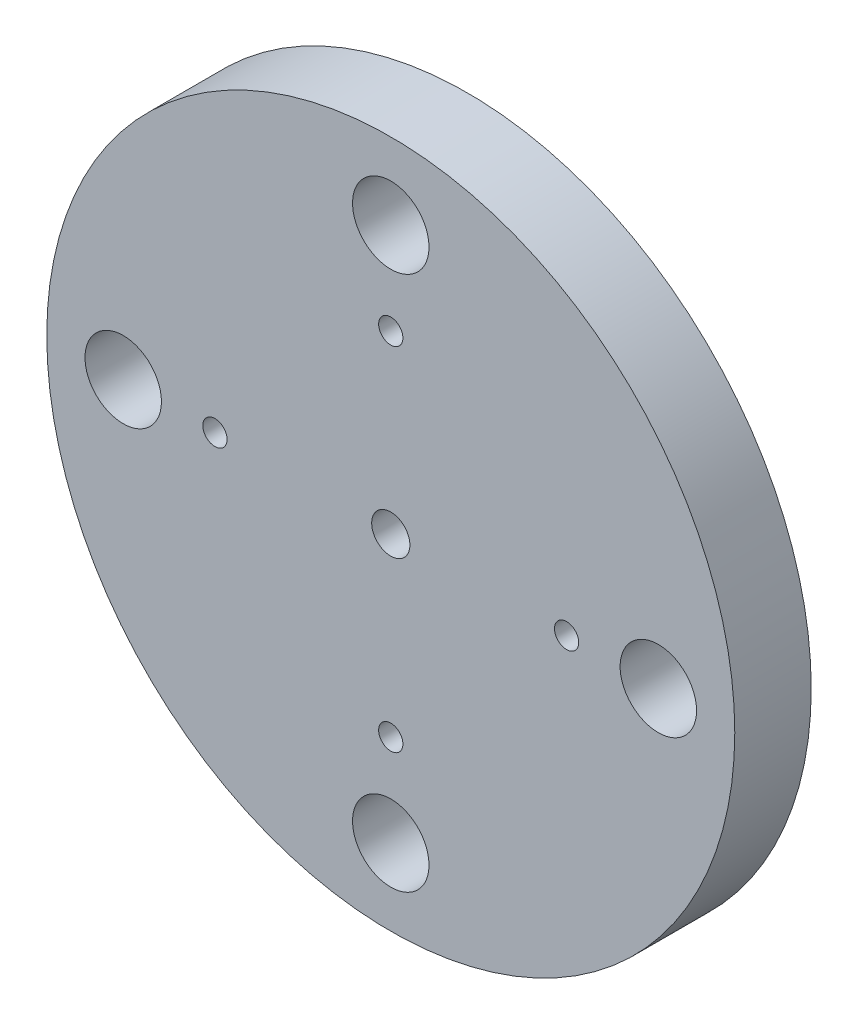
SolidWorks part; units mm, degrees
ref_plane "Front Plane" through (0, 0, 0) normal (0, 0, 1) x (1, 0, 0)
ref_plane "Top Plane" through (0, 0, 0) normal (0, 1, 0) x (1, 0, 0)
ref_plane "Right Plane" through (0, 0, 0) normal (1, 0, 0) x (0, 0, -1)
sketch "Sketch2" plane through (0, 0, 0) normal (0, 0, 1) x (1, 0, 0)
  circle A0 centre (0, 0) radius 45
  dimension "D1" = 90
extrude "Boss-Extrude1" add sketch "Sketch2" along normal blind 10
sketch "Sketch3" plane through (0, 0, 0) normal (0, 0, -1) x (-1, 0, 0)
  circle A0 centre (0, 0) radius 2.5
  dimension "D1" = 5
extrude "Cut-Extrude1" cut sketch "Sketch3" against normal through all
sketch "Sketch4" plane through (0, 0, 10) normal (0, 0, 1) x (1, 0, 0)
  circle A0 centre (0, 35) radius 5
  circle A1 centre (35, 0) radius 5
  circle A2 centre (0, -35) radius 5
  circle A3 centre (-35, 0) radius 5
  point P12 (0, 0)
  dimension "D1" = 10
  dimension "D2" = 35
  dimension "D3" = 4
extrude "Cut-Extrude2" cut sketch "Sketch4" against normal blind 10
hole_wizard "1/8 (0.125) Diameter Hole1" positions "Sketch5" profile "Sketch6" hole size "1/8" standard "ANSI Inch" end condition through all
sketch "Sketch5" plane through (0, 0, 10) normal (0, 0, 1) x (1, 0, 0)
  point P0 (0, 23)
  point P7 (23, 0)
  point P8 (0, -23)
  point P9 (-23, 0)
  point P13 (0, 0)
  dimension "D1" = 23
  dimension "D2" = 4
sketch "Sketch6" plane through (0, 23, 10) normal (1, 0, 0) x (0, -1, 0)
  line L0 (0, 0) -> (0, 10)
  line L1 (0, 10) -> (1.5875, 10)
  line L2 (1.5875, 10) -> (1.5875, 0)
  line L5 (1.5875, 0) -> (0, 0)
  line L11 (0, -6.35) -> (0, 107.95) construction
  dimension "Thru Hole Dia." = 3.175
  dimension "Thru Hole Depth" = 10
